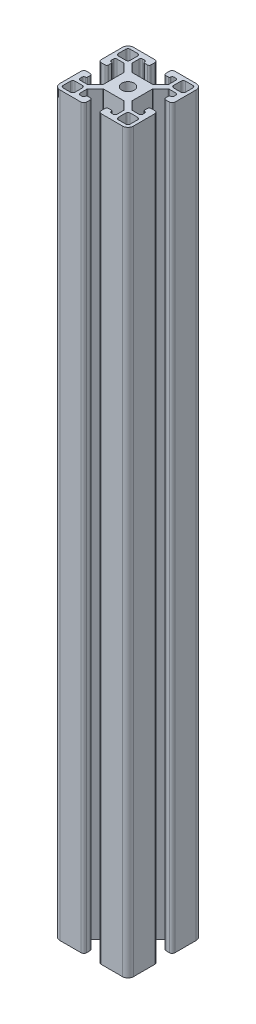
SolidWorks part; units mm, degrees
ref_plane "Front Plane" through (0, 0, 0) normal (0, 0, 1) x (1, 0, 0)
ref_plane "Top Plane" through (0, 0, 0) normal (0, 1, 0) x (1, 0, 0)
ref_plane "Right Plane" through (0, 0, 0) normal (1, 0, 0) x (0, 0, -1)
sketch "Sketch1" plane through (0, 0, 0) normal (0, 1, 0) x (1, 0, 0)
  line L0 (17, 11.78) -> (13, 11.78)
  line L1 (11.78, 13) -> (11.78, 17)
  line L2 (13, 18.22) -> (17, 18.22)
  line L3 (18.22, 17) -> (18.22, 13)
  line L4 (11.78, -17) -> (11.78, -13)
  line L5 (13, -11.78) -> (17, -11.78)
  line L6 (18.22, -13) -> (18.22, -17)
  line L7 (17, -18.22) -> (13, -18.22)
  line L8 (-17, -11.78) -> (-13, -11.78)
  line L9 (-11.78, -13) -> (-11.78, -17)
  line L10 (-13, -18.22) -> (-17, -18.22)
  line L11 (-18.22, -17) -> (-18.22, -13)
  line L12 (-18.22, 13) -> (-18.22, 17)
  line L13 (-17, 18.22) -> (-13, 18.22)
  line L14 (-11.78, 17) -> (-11.78, 13)
  line L15 (-13, 11.78) -> (-17, 11.78)
  line L16 (-9.8536, -11.9786) -> (-5.7714, -7.8964)
  line L17 (-5.4179, -7.75) -> (5.4179, -7.75)
  line L18 (5.7714, -7.8964) -> (9.8536, -11.9786)
  line L19 (11.9786, -9.8536) -> (7.8964, -5.7714)
  line L20 (7.75, -5.4179) -> (7.75, 5.4179)
  line L21 (7.8964, 5.7714) -> (11.9786, 9.8536)
  line L22 (12.3321, 10) -> (16, 10)
  line L23 (17, 9) -> (17, 8)
  line L24 (15.5, 6.5) -> (15.5, 5)
  line L25 (16.5, 4) -> (18.5, 4)
  line L26 (4, 18.5) -> (4, 16.5)
  line L27 (5, 15.5) -> (6.5, 15.5)
  line L28 (8, 17) -> (9, 17)
  line L29 (10, 16) -> (10, 12.3321)
  line L30 (9.8536, 11.9786) -> (5.7714, 7.8964)
  line L31 (5.4179, 7.75) -> (-5.4179, 7.75)
  line L32 (-5.7714, 7.8964) -> (-9.8536, 11.9786)
  line L33 (-11.9786, 9.8536) -> (-7.8964, 5.7714)
  line L34 (-7.75, 5.4179) -> (-7.75, -5.4179)
  line L35 (-7.8964, -5.7714) -> (-11.9786, -9.8536)
  line L36 (5.5, 20) -> (17, 20)
  line L37 (20, 5.5) -> (20, 17)
  line L38 (12.3321, -10) -> (16, -10)
  line L39 (17, -9) -> (17, -8)
  line L40 (15.5, -6.5) -> (15.5, -5)
  line L41 (16.5, -4) -> (18.5, -4)
  line L42 (4, -18.5) -> (4, -16.5)
  line L43 (5, -15.5) -> (6.5, -15.5)
  line L44 (8, -17) -> (9, -17)
  line L45 (10, -16) -> (10, -12.3321)
  line L46 (5.5, -20) -> (17, -20)
  line L47 (20, -5.5) -> (20, -17)
  line L48 (-12.3321, 10) -> (-16, 10)
  line L49 (-17, 9) -> (-17, 8)
  line L50 (-15.5, 6.5) -> (-15.5, 5)
  line L51 (-16.5, 4) -> (-18.5, 4)
  line L52 (-4, 18.5) -> (-4, 16.5)
  line L53 (-5, 15.5) -> (-6.5, 15.5)
  line L54 (-8, 17) -> (-9, 17)
  line L55 (-10, 16) -> (-10, 12.3321)
  line L56 (-5.5, 20) -> (-17, 20)
  line L57 (-20, 5.5) -> (-20, 17)
  line L58 (-12.3321, -10) -> (-16, -10)
  line L59 (-17, -9) -> (-17, -8)
  line L60 (-15.5, -6.5) -> (-15.5, -5)
  line L61 (-16.5, -4) -> (-18.5, -4)
  line L62 (-4, -18.5) -> (-4, -16.5)
  line L63 (-5, -15.5) -> (-6.5, -15.5)
  line L64 (-8, -17) -> (-9, -17)
  line L65 (-10, -16) -> (-10, -12.3321)
  line L66 (-5.5, -20) -> (-17, -20)
  line L67 (-20, -5.5) -> (-20, -17)
  arc A1 (11.78, 13) -> (13, 11.78) centre (13, 13) ccw
  arc A2 (13, 18.22) -> (11.78, 17) centre (13, 17) ccw
  arc A3 (18.22, 17) -> (17, 18.22) centre (17, 17) ccw
  arc A4 (17, 11.78) -> (18.22, 13) centre (17, 13) ccw
  arc A5 (13, -11.78) -> (11.78, -13) centre (13, -13) ccw
  arc A6 (18.22, -13) -> (17, -11.78) centre (17, -13) ccw
  arc A7 (17, -18.22) -> (18.22, -17) centre (17, -17) ccw
  arc A8 (11.78, -17) -> (13, -18.22) centre (13, -17) ccw
  arc A9 (-11.78, -13) -> (-13, -11.78) centre (-13, -13) ccw
  arc A10 (-13, -18.22) -> (-11.78, -17) centre (-13, -17) ccw
  arc A11 (-18.22, -17) -> (-17, -18.22) centre (-17, -17) ccw
  arc A12 (-17, -11.78) -> (-18.22, -13) centre (-17, -13) ccw
  arc A13 (-17, 18.22) -> (-18.22, 17) centre (-17, 17) ccw
  arc A14 (-11.78, 17) -> (-13, 18.22) centre (-13, 17) ccw
  arc A15 (-13, 11.78) -> (-11.78, 13) centre (-13, 13) ccw
  arc A16 (-18.22, 13) -> (-17, 11.78) centre (-17, 13) ccw
  circle A17 centre (0, 0) radius 3.35
  arc A18 (-9.8536, -11.9786) -> (-10, -12.3321) centre (-9.5, -12.3321) ccw
  arc A19 (-5.4179, -7.75) -> (-5.7714, -7.8964) centre (-5.4179, -8.25) ccw
  arc A20 (5.7714, -7.8964) -> (5.4179, -7.75) centre (5.4179, -8.25) ccw
  arc A21 (10, -12.3321) -> (9.8536, -11.9786) centre (9.5, -12.3321) ccw
  arc A22 (11.9786, -9.8536) -> (12.3321, -10) centre (12.3321, -9.5) ccw
  arc A23 (7.75, -5.4179) -> (7.8964, -5.7714) centre (8.25, -5.4179) ccw
  arc A24 (7.8964, 5.7714) -> (7.75, 5.4179) centre (8.25, 5.4179) ccw
  arc A25 (12.3321, 10) -> (11.9786, 9.8536) centre (12.3321, 9.5) ccw
  arc A26 (17, 9) -> (16, 10) centre (16, 9) ccw
  arc A27 (16, 7) -> (17, 8) centre (16, 8) ccw
  arc A28 (16, 7) -> (15.5, 6.5) centre (16, 6.5) ccw
  arc A29 (15.5, 5) -> (16.5, 4) centre (16.5, 5) ccw
  arc A30 (4, 16.5) -> (5, 15.5) centre (5, 16.5) ccw
  arc A31 (6.5, 15.5) -> (7, 16) centre (6.5, 16) ccw
  arc A32 (8, 17) -> (7, 16) centre (8, 16) ccw
  arc A33 (10, 16) -> (9, 17) centre (9, 16) ccw
  arc A34 (9.8536, 11.9786) -> (10, 12.3321) centre (9.5, 12.3321) ccw
  arc A35 (5.4179, 7.75) -> (5.7714, 7.8964) centre (5.4179, 8.25) ccw
  arc A36 (-5.7714, 7.8964) -> (-5.4179, 7.75) centre (-5.4179, 8.25) ccw
  arc A37 (-10, 12.3321) -> (-9.8536, 11.9786) centre (-9.5, 12.3321) ccw
  arc A38 (-11.9786, 9.8536) -> (-12.3321, 10) centre (-12.3321, 9.5) ccw
  arc A39 (-7.75, 5.4179) -> (-7.8964, 5.7714) centre (-8.25, 5.4179) ccw
  arc A40 (-7.8964, -5.7714) -> (-7.75, -5.4179) centre (-8.25, -5.4179) ccw
  arc A41 (-12.3321, -10) -> (-11.9786, -9.8536) centre (-12.3321, -9.5) ccw
  arc A42 (20, 17) -> (17, 20) centre (17, 17) ccw
  arc A43 (5.5, 20) -> (4, 18.5) centre (5.5, 18.5) ccw
  arc A44 (18.5, 4) -> (20, 5.5) centre (18.5, 5.5) ccw
  arc A45 (16, -10) -> (17, -9) centre (16, -9) ccw
  arc A46 (17, -8) -> (16, -7) centre (16, -8) ccw
  arc A47 (15.5, -6.5) -> (16, -7) centre (16, -6.5) ccw
  arc A48 (16.5, -4) -> (15.5, -5) centre (16.5, -5) ccw
  arc A49 (5, -15.5) -> (4, -16.5) centre (5, -16.5) ccw
  arc A50 (7, -16) -> (6.5, -15.5) centre (6.5, -16) ccw
  arc A51 (7, -16) -> (8, -17) centre (8, -16) ccw
  arc A52 (9, -17) -> (10, -16) centre (9, -16) ccw
  arc A53 (4, -18.5) -> (5.5, -20) centre (5.5, -18.5) ccw
  arc A54 (20, -5.5) -> (18.5, -4) centre (18.5, -5.5) ccw
  arc A55 (17, -20) -> (20, -17) centre (17, -17) ccw
  arc A56 (-16, 10) -> (-17, 9) centre (-16, 9) ccw
  arc A57 (-17, 8) -> (-16, 7) centre (-16, 8) ccw
  arc A58 (-15.5, 6.5) -> (-16, 7) centre (-16, 6.5) ccw
  arc A59 (-16.5, 4) -> (-15.5, 5) centre (-16.5, 5) ccw
  arc A60 (-5, 15.5) -> (-4, 16.5) centre (-5, 16.5) ccw
  arc A61 (-7, 16) -> (-6.5, 15.5) centre (-6.5, 16) ccw
  arc A62 (-7, 16) -> (-8, 17) centre (-8, 16) ccw
  arc A63 (-9, 17) -> (-10, 16) centre (-9, 16) ccw
  arc A64 (-4, 18.5) -> (-5.5, 20) centre (-5.5, 18.5) ccw
  arc A65 (-20, 5.5) -> (-18.5, 4) centre (-18.5, 5.5) ccw
  arc A66 (-17, 20) -> (-20, 17) centre (-17, 17) ccw
  arc A67 (-17, -9) -> (-16, -10) centre (-16, -9) ccw
  arc A68 (-16, -7) -> (-17, -8) centre (-16, -8) ccw
  arc A69 (-16, -7) -> (-15.5, -6.5) centre (-16, -6.5) ccw
  arc A70 (-15.5, -5) -> (-16.5, -4) centre (-16.5, -5) ccw
  arc A71 (-4, -16.5) -> (-5, -15.5) centre (-5, -16.5) ccw
  arc A72 (-6.5, -15.5) -> (-7, -16) centre (-6.5, -16) ccw
  arc A73 (-8, -17) -> (-7, -16) centre (-8, -16) ccw
  arc A74 (-10, -16) -> (-9, -17) centre (-9, -16) ccw
  arc A75 (-5.5, -20) -> (-4, -18.5) centre (-5.5, -18.5) ccw
  arc A76 (-18.5, -4) -> (-20, -5.5) centre (-18.5, -5.5) ccw
  arc A77 (-20, -17) -> (-17, -20) centre (-17, -17) ccw
  point P3 (0, 0.001)
  point P4 (0.001, 0.001)
  point P5 (0.001, 0)
extrude "Boss-Extrude1" add sketch "Sketch1" along normal blind 400
